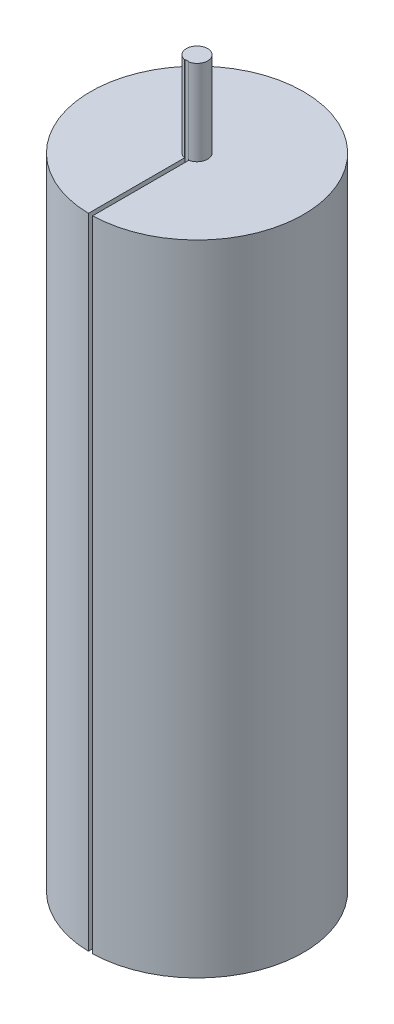
SolidWorks part; units mm, degrees
ref_plane "Front Plane" through (0, 0, 0) normal (0, 0, 1) x (1, 0, 0)
ref_plane "Top Plane" through (0, 0, 0) normal (0, 1, 0) x (1, 0, 0)
ref_plane "Right Plane" through (0, 0, 0) normal (1, 0, 0) x (0, 0, -1)
sketch "Sketch1" plane through (0, 0, 0) normal (0, 1, 0) x (1, 0, 0)
  circle A0 centre (0, 0) radius 25
  dimension "D1" = 50
extrude "Boss-Extrude1" add sketch "Sketch1" along normal blind 150
sketch "Sketch2" plane through (0, 150, 0) normal (0, 1, 0) x (1, 0, 0)
  circle A0 centre (0, 0) radius 2.5
  dimension "D1" = 5
extrude "Boss-Extrude2" add sketch "Sketch2" along normal blind 20
sketch "Sketch3" plane through (0, 0, 0) normal (0, -1, 0) x (1, 0, 0)
  line L1 (-0.5, 28.9877) -> (0.5, 28.9877)
  line L2 (-0.5, 28.9877) -> (-0.5, 2.362)
  line L3 (-0.5, 2.362) -> (0.5, 2.362)
  line L4 (0.5, 28.9877) -> (0.5, 2.362)
  point P4 (0, 2.362)
  dimension "D1" = 26.6258
  dimension "D2" = 1
extrude "Cut-Extrude1" cut sketch "Sketch3" against normal through all
